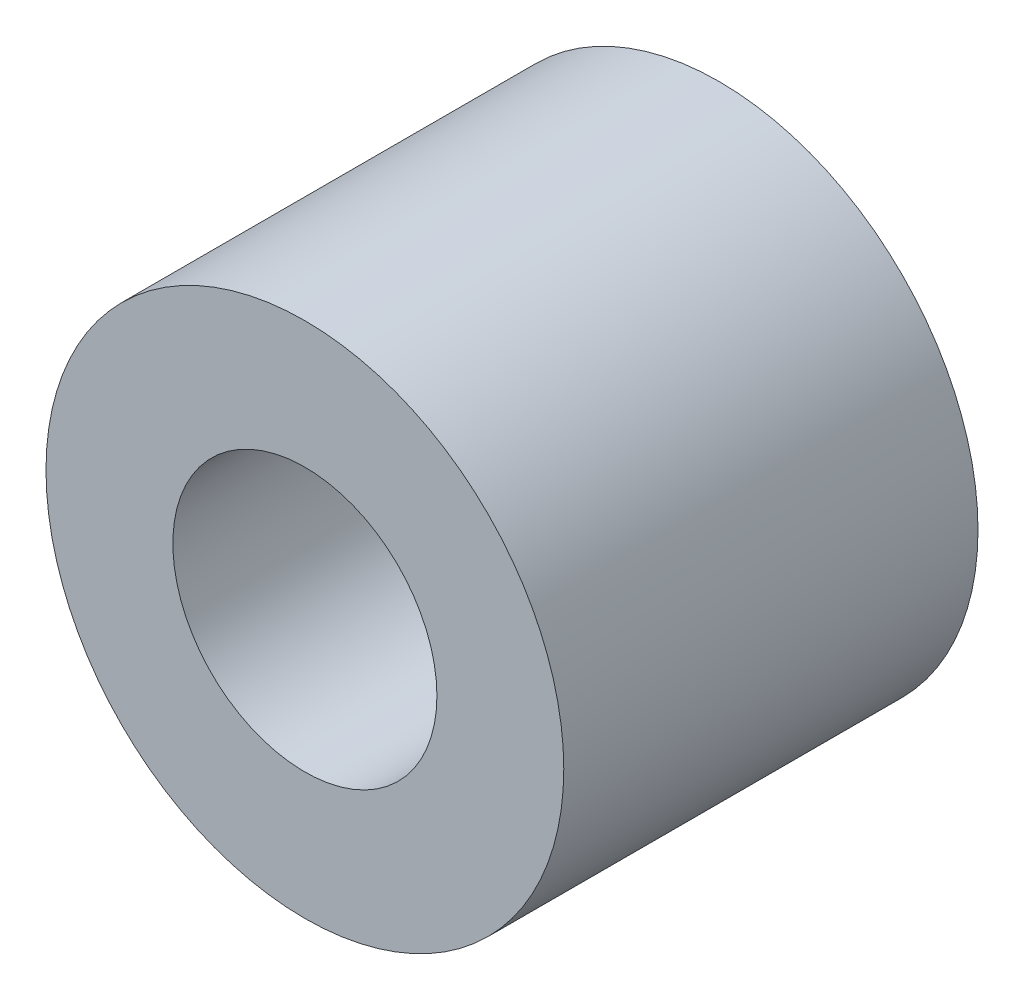
SolidWorks part; units mm, degrees
ref_plane "Front Plane" through (0, 0, 0) normal (0, 0, 1) x (1, 0, 0)
ref_plane "Top Plane" through (0, 0, 0) normal (0, 1, 0) x (1, 0, 0)
ref_plane "Right Plane" through (0, 0, 0) normal (1, 0, 0) x (0, 0, -1)
sketch "Sketch0" plane through (0, 0, 0) normal (0, 1, 0) x (0, 0, -1)
  line L0 (-8, 0) -> (8, 0) construction
  line L1 (-8, 0) -> (-8, 10) construction
  line L2 (-8, 10) -> (8, 10) construction
  line L3 (8, 10) -> (8, 0) construction
  line L4 (-8, -10) -> (-8, 10) construction
  line L6 (-8, 5.1) -> (-8, -5.1) construction
  point P2 (0, 0)
  point P8 (-8, 0)
  point P11 (-8, 0)
  point P12 (-8, 5.1)
  point P13 (-8, -5.1)
  point P15 (8, 10)
  point P17 (-8, 10)
  dimension "Length" = 16
  dimension "OD" = 20
  dimension "ID" = 10.2
sketch "Sketch1" plane through (0, 0, 0) normal (1, 0, 0) x (0, 0, -1)
  line L0 (8, 0) -> (-8, 0) construction
  line L1 (-8, 0) -> (8, 0)
  line L2 (-8, 0) -> (-8, 10)
  line L3 (-8, 10) -> (8, 10)
  line L4 (8, 0) -> (8, 10)
  line L5 (-8, 0) -> (8, 10) construction
  line L6 (-8, 10) -> (8, 0) construction
  point P0 (-8, 0)
  dimension "D1" = 20
  dimension "Length" = 16
sketch "Sketch5" plane through (0, 0, 0) normal (0, 1, 0) x (0, 0, -1)
  line L1 (-8, 10) -> (8, 10)
  line L2 (-8, 10) -> (-8, 0)
  line L3 (-8, 0) -> (8, 0)
  line L4 (8, 10) -> (8, 0)
revolve "Revolve1" add sketch "Sketch5" angle 360 about L0
sketch "Sketch7" plane through (0, 0, 8) normal (0, 0, 1) x (1, 0, 0)
  circle A0 centre (0, 0) radius 5.1
extrude "Cut-Extrude1" cut sketch "Sketch7" against normal through all
equation "\"D1@Sketch1\"=\"od@sketch0\""
